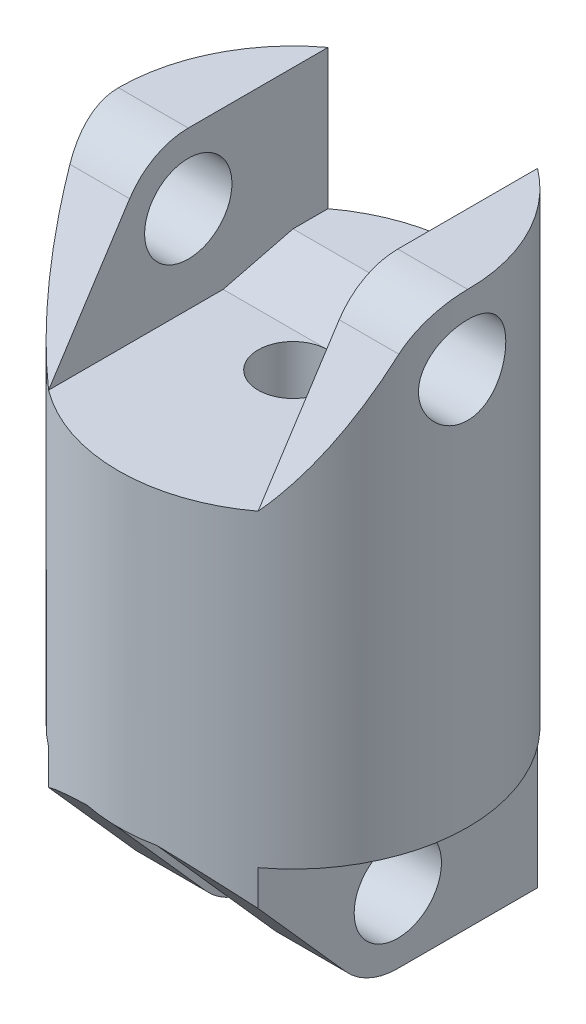
SolidWorks part; units mm, degrees
ref_plane "Front Plane" through (0, 0, 0) normal (0, 0, 1) x (1, 0, 0)
ref_plane "Top Plane" through (0, 0, 0) normal (0, 1, 0) x (1, 0, 0)
ref_plane "Right Plane" through (0, 0, 0) normal (1, 0, 0) x (0, 0, -1)
sketch "Sketch1" plane through (0, 0, 0) normal (0, 1, 0) x (1, 0, 0)
  circle A0 centre (0, 0) radius 12.7
  dimension "D1" = 25.4
extrude "Boss-Extrude1" add sketch "Sketch1" along normal blind 45.3136
sketch "Sketch2" plane through (0, 45.3136, 0) normal (0, 1, 0) x (1, 0, 0)
  line L0 (7.62, 10.16) -> (7.62, -10.16)
  line L1 (-7.62, 10.16) -> (-7.62, -10.16)
  arc A0 (-7.62, -10.16) -> (7.62, -10.16) centre (0, 0) ccw
  arc A1 (7.62, 10.16) -> (-7.62, 10.16) centre (0, 0) ccw
  dimension "D2" = 25.4
  dimension "D1" = 7.62
  dimension "D3" = 7.62
extrude "Cut-Extrude1" cut sketch "Sketch2" against normal blind 11.43
sketch "Sketch3" plane through (0, 0, 0) normal (0, -1, 0) x (1, 0, 0)
  line L0 (-2.54, 12.4434) -> (-2.54, -12.4434)
  line L1 (-7.62, 10.16) -> (-7.62, -10.16)
  line L2 (2.54, 12.4434) -> (2.54, -12.4434)
  line L3 (7.62, 10.16) -> (7.62, -10.16)
  arc A0 (-7.62, 10.16) -> (-7.62, -10.16) centre (0, 0) ccw
  arc A1 (-2.54, -12.4434) -> (2.54, -12.4434) centre (0, 0) ccw
  arc A2 (7.62, -10.16) -> (7.62, 10.16) centre (0, 0) ccw
  arc A3 (2.54, 12.4434) -> (-2.54, 12.4434) centre (0, 0) ccw
  dimension "D1" = 25.4
  dimension "D2" = 2.54
  dimension "D3" = 5.08
  dimension "D4" = 2.54
  dimension "D5" = 5.08
extrude "Cut-Extrude2" cut sketch "Sketch3" against normal blind 11.43
sketch "Sketch4" plane through (-7.62, 0, 0) normal (1, 0, 0) x (0, 0, -1)
  line L0 (10.16, 45.3136) -> (-10.16, 45.3136) construction
  line L5 (10.16, 0) -> (-10.16, 0) construction
  line L6 (0, 45.3136) -> (-10.16, 45.3136)
  line L7 (-10.16, 45.3136) -> (-10.16, 33.8836)
  line L10 (-4.2649, 42.9935) -> (-10.16, 33.8836)
  line L11 (-3.7964, 1.7046) -> (-12.4434, 11.43)
  line L12 (-12.4434, 11.43) -> (-12.4434, 0)
  line L13 (-12.4434, 0) -> (-10.16, 0) construction
  line L14 (-12.4434, 11.43) -> (-12.4434, 0) construction
  line L15 (-12.4434, 0) -> (0, 0)
  circle A0 centre (0, 40.2336) radius 3.175
  circle A2 centre (0, 5.08) radius 3.175
  arc A3 (0, 45.3136) -> (-4.2649, 42.9935) centre (0, 40.2336) ccw
  arc A4 (0, 0) -> (-3.7964, 1.7046) centre (0, 5.08) cw
  dimension "D1" = 6.35
  dimension "D3" = 6.35
  dimension "D2" = 5.08
  dimension "D4" = 5.08
  dimension "D5" = 0
extrude "Cut-Extrude3" cut sketch "Sketch4" against normal through all both and the other way through all
sketch "Sketch5" plane through (0, 33.8836, 0) normal (0, 1, 0) x (1, 0, 0)
  circle A0 centre (0, 0) radius 2.54
  dimension "D1" = 5.08
extrude "Cut-Extrude4" cut sketch "Sketch5" against normal through all
sketch "Sketch6" plane through (-7.62, 0, 0) normal (1, 0, 0) x (0, 0, -1)
  line L0 (2.54, 33.8836) -> (10.16, 33.8836)
  line L1 (10.16, 33.8836) -> (-10.16, 33.8836) construction
  line L2 (10.16, 33.8836) -> (10.16, 45.3136) construction
  line L3 (10.16, 33.8836) -> (10.16, 35.1536)
  line L4 (10.16, 35.1536) -> (7.62, 35.1536)
  line L5 (7.62, 35.1536) -> (2.54, 33.8836)
  point P7 (0, 33.8836)
  dimension "D1" = 2.54
  dimension "D2" = 1.27
  dimension "D3" = 2.54
extrude "Boss-Extrude2" add sketch "Sketch6" along normal up to surface (15.24 mm away) up to face at (7.62, 40.2336, -3.175)
sketch "Sketch7" plane through (0, 33.8836, 0) normal (0, 1, 0) x (1, 0, 0)
  line L0 (-7.62, 10.16) -> (7.62, 10.16)
  arc A0 (-7.62, 10.16) -> (7.62, 10.16) centre (0, 0) cw
  arc M1 (7.62, 10.16) -> (-7.62, 10.16) centre (0, 0) ccw
  line M2 (-7.62, 10.16) -> (7.62, 10.16)
extrude "Boss-Extrude3" add sketch "Sketch7" along normal up to surface (1.27 mm away) contours M2 M1 up to face at (0, 35.1536, -8.89)
